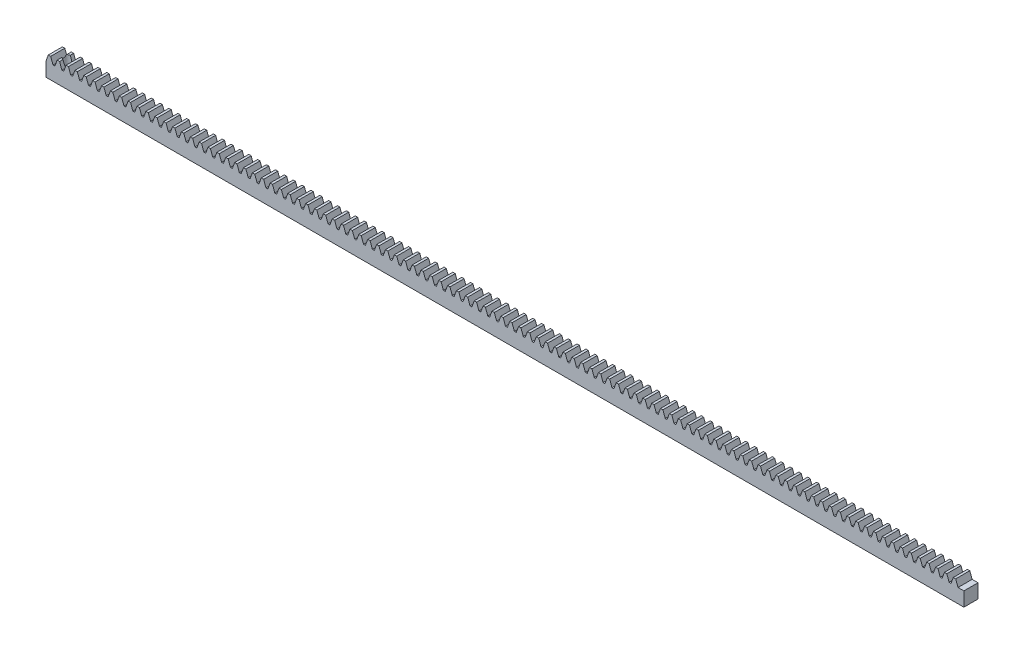
SolidWorks part; units mm, degrees
ref_plane "前视基准面" through (0, 0, 0) normal (0, 0, 1) x (1, 0, 0)
ref_plane "上视基准面" through (0, 0, 0) normal (0, 1, 0) x (1, 0, 0)
ref_plane "右视基准面" through (0, 0, 0) normal (1, 0, 0) x (0, 0, -1)
sketch "草图1" plane through (0, 0, 0) normal (0, 0, 1) x (1, 0, 0)
  line L1 (0, 0) -> (650, 0)
  line L2 (0, 0) -> (0, -10)
  line L3 (0, -10) -> (650, -10)
  line L4 (650, 0) -> (650, -10)
  dimension "D1" = 10
  dimension "L" = 650
extrude "拉伸1" add sketch "草图1" along normal blind 10
sketch "草图2" plane through (0, 0, 10) normal (0, 0, 1) x (1, 0, 0)
  line L0 (0, 0) -> (1.6379, 4.5)
  line L1 (1.6379, 4.5) -> (3.3236, 4.5)
  line L2 (3.3236, 4.5) -> (4.9614, 0)
  line L3 (650, 0) -> (0, 0) construction
  line L4 (0, 0) -> (4.9614, 0)
  line L5 (0.9099, 2.5) -> (4.0515, 2.5) construction
  dimension "D2" = 70
  dimension "alpha" = 110
  dimension "ha" = 2
  dimension "hf" = 2.5
  dimension "S" = 3.1416
extrude "拉伸2" add sketch "草图2" against normal up to surface (10 mm away) up to face at (325, -5, 0)
pattern_linear "阵列(线性)1" count 103 spacing 6.2832 along (1, 0, 0) of "拉伸2"
sketch "草图3" plane through (0, -10, 0) normal (0, -1, 0) x (1, 0, 0)
  line L0 (0, 5) -> (26.9765, 5) construction
  line L1 (0, 10) -> (0, 0) construction
  circle A0 centre (10, 5) radius 2.6
  dimension "D2" = 5.2
  dimension "D1" = 10
extrude "切除-拉伸1" cut sketch "草图3" against normal up to next
equation "\"d\"=\"S@草图2\" * 2"
equation "\"z\"= int(  \"L@草图1\" / (  \"S@草图2\" * 2 ) + 0.5 )"
